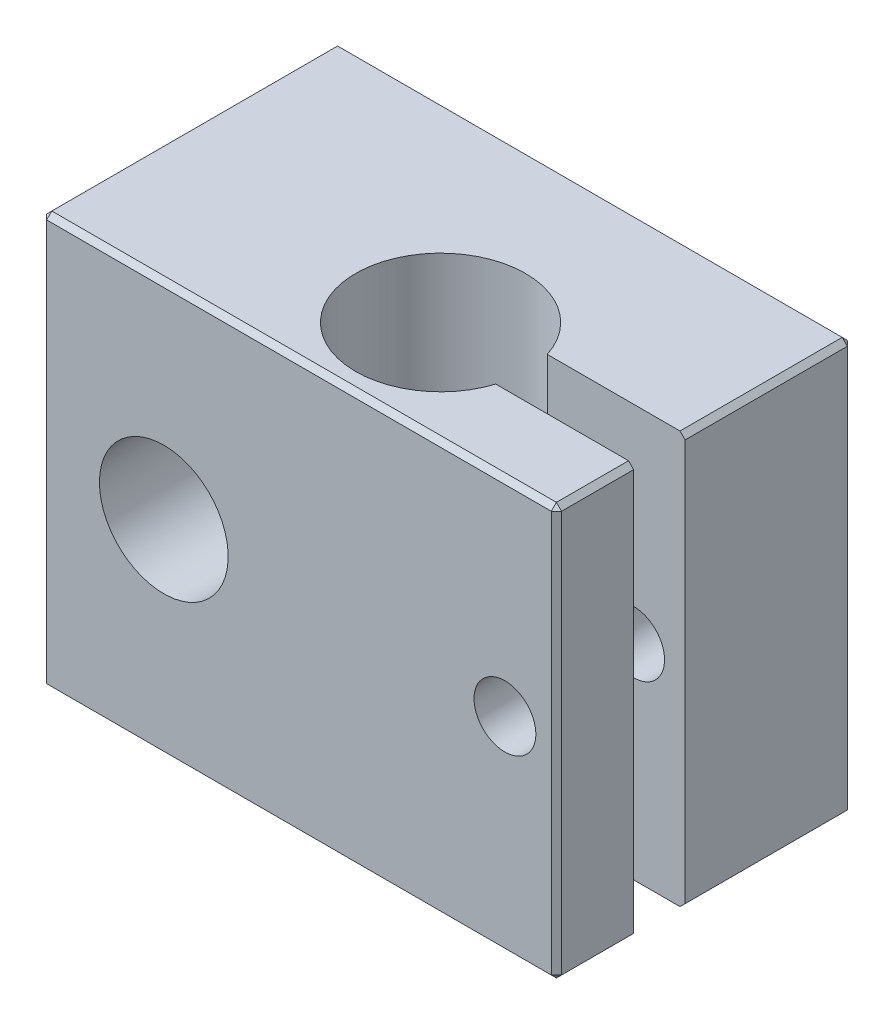
SolidWorks part; units mm, degrees
ref_plane "Спереди" through (0, 0, 0) normal (0, 0, 1) x (1, 0, 0)
ref_plane "Сверху" through (0, 0, 0) normal (0, 1, 0) x (1, 0, 0)
ref_plane "Справа" through (0, 0, 0) normal (1, 0, 0) x (0, 0, -1)
ref_plane "Плоскость4" through (0, 0, 0) normal (0, 0, -1) x (-1, 0, 0)
sketch "Эскиз1" plane through (0, 0, 0) normal (0, 0, -1) x (-1, 0, 0)
  line L0 (-15.25, -8) -> (4.75, -8)
  line L1 (4.75, -8) -> (4.75, 8)
  line L2 (4.75, 8) -> (-15.25, 8)
  line L3 (-15.25, 8) -> (-15.25, -8)
extrude "Бобышка-Вытянуть1" add sketch "Эскиз1" against normal blind 11.5
sketch "Эскиз2" plane through (0, 8, 0) normal (0, 1, 0) x (-1, 0, 0)
  line L0 (-15.25, 8.5) -> (-15.25, 6.5)
  line L1 (-15.25, 6.5) -> (-9.8948, 6.5)
  line L2 (-9.8948, 8.5) -> (-15.25, 8.5)
  arc A0 (-9.8948, 6.5) -> (-9.8948, 8.5) centre (-6.75, 7.5) cw
extrude "Вырез-Вытянуть1" cut sketch "Эскиз2" against normal through all
ref_plane "Плоскость5" through (0, 0, 7.5) normal (0, 0, 1) x (1, 0, 0)
sketch "Эскиз3" plane through (0, 0, 7.5) normal (0, 0, 1) x (1, 0, 0)
  line L0 (10.05, 8) -> (6.75, 8)
  line L1 (6.75, 8) -> (6.75, -8)
  line L2 (6.75, -8) -> (10.05, -8)
  line L3 (10.05, -8) -> (10.05, 8)
  line L4 (6.75, 8) -> (6.75, -8) construction
revolve "Вырез-Повернуть1" cut sketch "Эскиз3" angle 360 about L4
hole_wizard "Диаметр отверстия Ø5.0 (5)1" positions "Эскиз5" profile "Эскиз4" hole size "Ø5.0" standard "Ansi Metric"
sketch "Эскиз5" plane through (0, 0, 0) normal (0, 0, -1) x (-1, 0, 0)
  point P0 (0, 0)
sketch "Эскиз4" plane through (0, 0, 0) normal (1, 0, 0) x (0, 1, 0)
  line L0 (0, 0) -> (0, 11.5)
  line L1 (0, 11.5) -> (2.5, 11.5)
  line L2 (2.5, 11.5) -> (2.5, 0)
  line L5 (2.5, 0) -> (0, 0)
  line L11 (0, -6.35) -> (0, 107.95) construction
  dimension "Диаметр сквозного отверстия" = 5
  dimension "Глубина сквозного отверстия" = 11.5
hole_wizard "Диаметр отверстия Ø1.6 (1.6)1" positions "Эскиз7" profile "Эскиз6" hole size "Ø1.6" standard "Ansi Metric"
sketch "Эскиз7" plane through (0, 0, 8.5) normal (0, 0, -1) x (-1, 0, 0)
  point P0 (-13.25, 0)
sketch "Эскиз6" plane through (13.25, 0, 8.5) normal (1, 0, 0) x (0, 1, 0)
  line L0 (0, 0) -> (0, 3)
  line L1 (0, 3) -> (0.8, 3)
  line L2 (0.8, 3) -> (0.8, 0)
  line L5 (0.8, 0) -> (0, 0)
  line L11 (0, -6.35) -> (0, 107.95) construction
  dimension "Диаметр сквозного отверстия" = 1.6
  dimension "Глубина сквозного отверстия" = 3
hole_wizard "Диаметр отверстия Ø2.4 (2.4)1" positions "Эскиз9" profile "Эскиз8" hole size "Ø2.4" standard "Ansi Metric"
sketch "Эскиз9" plane through (0, 0, 0) normal (0, 0, -1) x (-1, 0, 0)
  point P0 (-13.25, 0)
sketch "Эскиз8" plane through (13.25, 0, 0) normal (1, 0, 0) x (0, 1, 0)
  line L0 (0, 0) -> (0, 11.5)
  line L1 (0, 11.5) -> (1.2, 11.5)
  line L2 (1.2, 11.5) -> (1.2, 0)
  line L5 (1.2, 0) -> (0, 0)
  line L11 (0, -6.35) -> (0, 107.95) construction
  dimension "Диаметр сквозного отверстия" = 2.4
  dimension "Глубина сквозного отверстия" = 11.5
hole_wizard "Диаметр отверстия Ø2.05 (2.05)1" positions "Эскиз11" profile "Эскиз10" hole size "Ø2.05" standard "Ansi Metric"
sketch "Эскиз11" plane through (0, -8, 0) normal (0, -1, 0) x (-1, 0, 0)
  point P0 (1.25, -6.5)
sketch "Эскиз10" plane through (-1.25, -8, 6.5) normal (1, 0, 0) x (0, 0, -1)
  line L0 (0, 0) -> (0, 5.1159)
  line L1 (0, 5.1159) -> (1.025, 4.5)
  line L2 (1.025, 4.5) -> (1.025, 0)
  line L5 (1.025, 0) -> (0, 0)
  line L10 (0, 5.1159) -> (-1.025, 4.5) construction
  line L11 (0, -6.35) -> (0, 107.95) construction
  dimension "Диаметр отверстия" = 2.05
  dimension "Глубина отверстия" = 4.5
  dimension "Угол заточки сверла" = 118
hole_wizard "Отверстие обработанное метчиком M2x0.41" positions "Эскиз13" profile "Эскиз12" tap size "M2x0.4" standard "Ansi Metric"
sketch "Эскиз13" plane through (0, -8, 0) normal (0, -1, 0) x (-1, 0, 0)
  point P0 (2.25, -9)
sketch "Эскиз12" plane through (-2.25, -8, 9) normal (1, 0, 0) x (0, 0, -1)
  line L0 (0, 0) -> (0, 4.5)
  line L1 (0, 4.5) -> (0.5, 4.5)
  line L2 (0.5, 4.5) -> (0.5, 2)
  line L3 (0.5, 2) -> (1, 2)
  line L4 (1, 2) -> (1, 0)
  line L5 (1, 0) -> (0, 0)
  line L10 (0, 4.5) -> (-0.5, 4.5) construction
  line L11 (0, -6.35) -> (0, 107.95) construction
  dimension "Диаметр сверла" = 1
  dimension "Глубина сверла" = 4.5
  dimension "Диаметр резьбы" = 2
  dimension "Глубина резьбы" = 2
  dimension "Угол заточки сверла" = 180
chamfer "Фаска1" distance 0.2 angle 45 14 edges at (15.25, 8, 3.25) (15.25, -8, 3.25) (15.25, 0, 0) (5.25, 8, 0) (5.25, -8, 0) (-4.75, 0, 0) (15.25, 8, 10) (-4.75, 8, 5.75) (5.25, 8, 11.5) (15.25, -8, 10) (-4.75, -8, 5.75) (15.25, 0, 11.5) (-4.75, 0, 11.5) (5.25, -8, 11.5)
